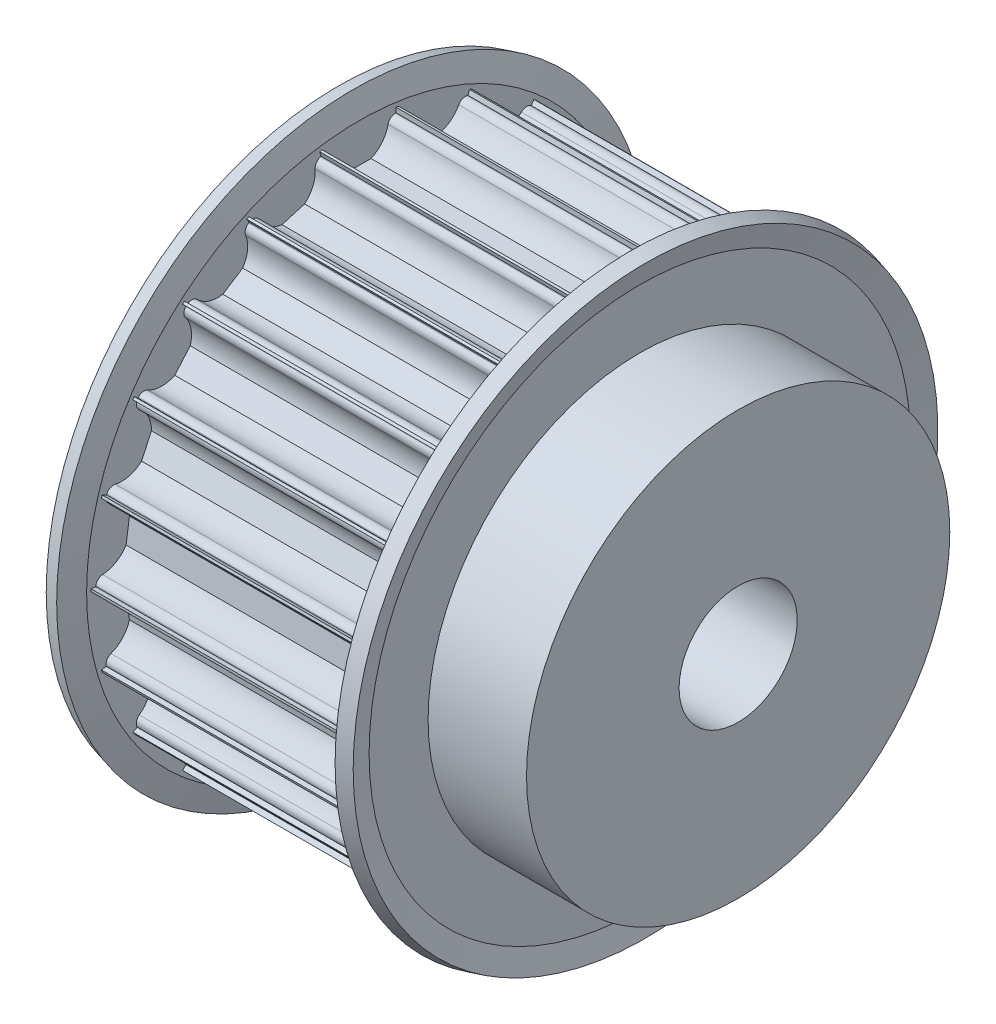
SolidWorks part; units mm, degrees
ref_plane "Front Plane" through (0, 0, 0) normal (0, 0, 1) x (1, 0, 0)
ref_plane "Top Plane" through (0, 0, 0) normal (0, 1, 0) x (1, 0, 0)
ref_plane "Right Plane" through (0, 0, 0) normal (1, 0, 0) x (0, 0, -1)
sketch "Sketch1" plane through (0, 0, 0) normal (0, 0, 1) x (1, 0, 0)
  line L0 (0, 0) -> (12.9639, 0) construction
  line L1 (0, 6) -> (0, 27.25)
  line L2 (0, 27.25) -> (30, 27.25)
  line L3 (30, 27.25) -> (30, 21.5)
  line L4 (30, 21.5) -> (40, 21.5)
  line L5 (40, 21.5) -> (40, 6)
  line L6 (40, 6) -> (0, 6)
  dimension "D1" = 6
  dimension "D2" = 27.25
  dimension "D3" = 30
  dimension "D4" = 10
  dimension "D5" = 15.5
revolve "Revolve1" add sketch "Sketch1" angle 360 about L0
sketch "Sketch2" plane through (0, 0, 0) normal (-1, 0, 0) x (0, 0, 1)
  line L0 (-3.6742, 26.5) -> (-3.75, 26.5)
  line L1 (-3.75, 26.5) -> (-3.75, 28.5)
  line L2 (-3.75, 28.5) -> (3.75, 28.5)
  line L3 (3.75, 28.5) -> (3.75, 26.5)
  line L4 (3.75, 26.5) -> (3.6742, 26.5)
  line L5 (-1.199, 23.75) -> (1.199, 23.75)
  arc A0 (2.9394, 25.9) -> (1.199, 23.75) centre (0, 26.5) cw
  arc A2 (2.9394, 25.9) -> (3.6742, 26.5) centre (3.6742, 25.75) cw
  arc A3 (-2.9394, 25.9) -> (-3.6742, 26.5) centre (-3.6742, 25.75) ccw
  arc A4 (-1.199, 23.75) -> (-2.9394, 25.9) centre (0, 26.5) cw
  point P3 (0, 28.5)
  point P11 (3, 26.5)
  point P14 (-3, 26.5)
  dimension "D2" = 3
  dimension "D5" = 0.75
  dimension "D1" = 26.5
  dimension "D3" = 7.5
  dimension "D4" = 2
  dimension "D6" = 2.75
extrude "Cut-Extrude1" cut sketch "Sketch2" against normal through all
pattern_circular "CirPattern1" count 22 over 360 about axis through (0, 0, 0) along (1, 0, 0) of "Cut-Extrude1"
sketch "Sketch3" plane through (0, 0, 0) normal (0, 0, 1) x (1, 0, 0)
  line L0 (30, 21.5) -> (28.5, 21.5)
  line L1 (28.5, 21.5) -> (28.5, 27.69)
  line L2 (28.5, 27.69) -> (29.1431, 30.09)
  line L3 (29.1431, 30.09) -> (30.592, 29.7018)
  line L4 (30.592, 29.7018) -> (30, 27.4925)
  line L5 (30, 27.4925) -> (30, 21.5)
  line L6 (40, 21.5) -> (30, 21.5) construction
  line L7 (15, 26.9539) -> (15, 10.5856) construction
  line L8 (0, 26.9539) -> (30, 26.9539) construction
  line L9 (0, 21.5) -> (1.5, 21.5)
  line L10 (0, 27.4925) -> (0, 21.5)
  line L11 (-0.592, 29.7018) -> (0, 27.4925)
  line L12 (0.8569, 30.09) -> (-0.592, 29.7018)
  line L13 (1.5, 27.69) -> (0.8569, 30.09)
  line L14 (1.5, 21.5) -> (1.5, 27.69)
  dimension "D1" = 15
  dimension "D2" = 2.4
  dimension "D3" = 1.5
  dimension "D4" = 6.19
revolve "Revolve2" add sketch "Sketch3" angle 360 about L0
